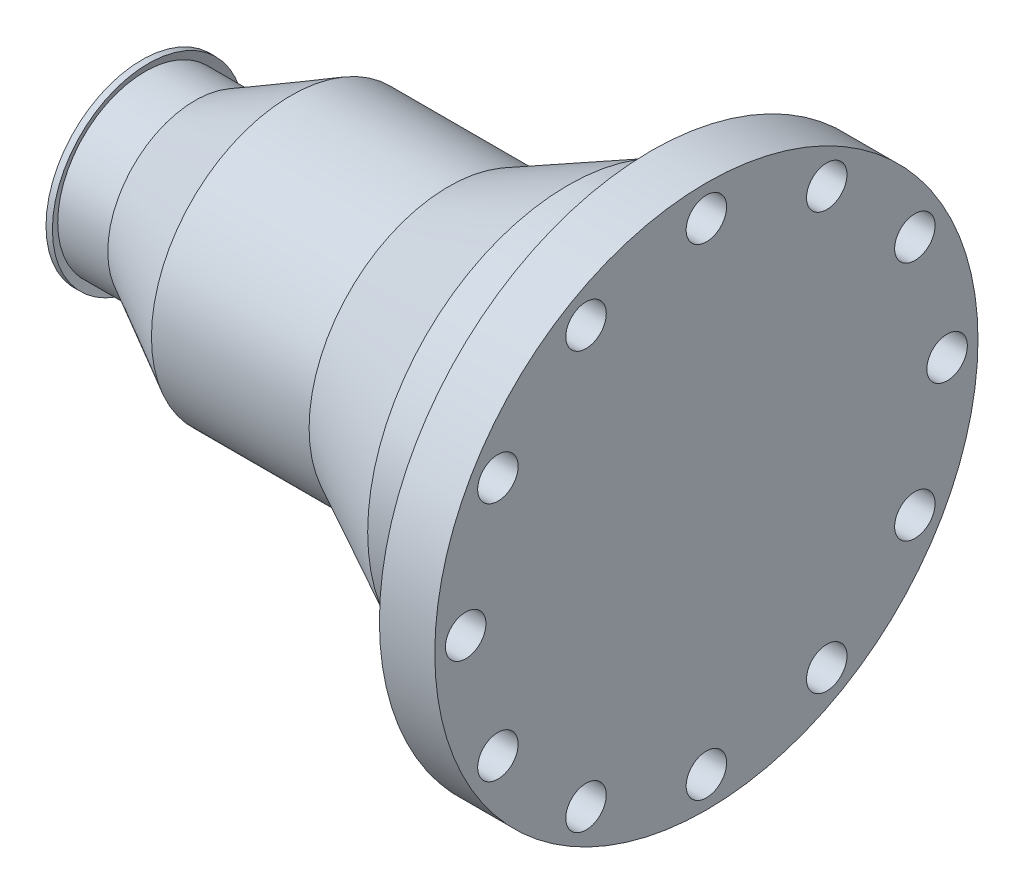
SolidWorks part; units mm, degrees
ref_plane "Спереди" through (0, 0, 0) normal (0, 0, 1) x (1, 0, 0)
ref_plane "Сверху" through (0, 0, 0) normal (0, 1, 0) x (1, 0, 0)
ref_plane "Справа" through (0, 0, 0) normal (1, 0, 0) x (0, 0, -1)
sketch "Эскиз1" plane through (0, 0, 0) normal (0, 0, 1) x (1, 0, 0)
  line L0 (0, 0) -> (265, 0)
  line L1 (0, 0) -> (0, 45)
  line L2 (0, 45) -> (3, 45)
  line L3 (3, 45) -> (1.5, 41)
  line L4 (1.5, 41) -> (25, 41)
  line L5 (25, 41) -> (70, 65.5)
  line L6 (70, 65.5) -> (144, 65.5)
  line L7 (144, 65.5) -> (200, 94)
  line L8 (200, 94) -> (220, 94)
  line L9 (220, 94) -> (220, 95)
  line L10 (220, 95) -> (239, 95)
  line L11 (239, 95) -> (239, 100)
  line L12 (239, 100) -> (239, 127.5)
  line L13 (239, 127.5) -> (265, 127.5)
  line L14 (265, 127.5) -> (265, 0)
revolve "Повернуть1" add sketch "Эскиз1" angle 360 about L0
sketch "Эскиз2" plane through (0, 0, 0) normal (0, 0, 1) x (1, 0, 0)
  line L0 (0, 0) -> (140, 0)
  line L1 (0, 0) -> (0, 31)
  line L2 (0, 45) -> (0, -45) construction
  line L3 (0, 31) -> (38, 31)
  line L4 (38, 31) -> (111.8808, 50.7963)
  line L5 (124.8206, 52.5839) -> (140, 52.5839)
  line L6 (140, 52.5839) -> (140, 0)
  arc A0 (111.8808, 50.7963) -> (124.8206, 52.5839) centre (125.4916, 0) cw
sketch "Эскиз3" plane through (0, 0, 0) normal (1, 0, 0) x (0, 0, -1)
  circle A0 centre (0, 113) radius 9.5
extrude "Вырез-Вытянуть1" cut sketch "Эскиз3" along normal through all
sketch "Эскиз4" plane through (0, 0, 0) normal (1, 0, 0) x (0, 0, -1)
  circle A0 centre (-56.5, 97.8609) radius 9.5
extrude "Вырез-Вытянуть2" cut sketch "Эскиз4" along normal through all
sketch "Эскиз5" plane through (0, 0, 0) normal (1, 0, 0) x (0, 0, -1)
  circle A0 centre (-97.8609, 56.5) radius 9.5
extrude "Вырез-Вытянуть3" cut sketch "Эскиз5" along normal through all
sketch "Эскиз6" plane through (0, 0, 0) normal (1, 0, 0) x (0, 0, -1)
  circle A0 centre (-113, 0) radius 9.5
extrude "Вырез-Вытянуть4" cut sketch "Эскиз6" along normal through all
sketch "Эскиз7" plane through (0, 0, 0) normal (1, 0, 0) x (0, 0, -1)
  circle A0 centre (-97.8609, -56.5) radius 9.5
extrude "Вырез-Вытянуть5" cut sketch "Эскиз7" along normal through all
sketch "Эскиз8" plane through (0, 0, 0) normal (1, 0, 0) x (0, 0, -1)
  circle A0 centre (-56.5, -97.8609) radius 9.5
extrude "Вырез-Вытянуть6" cut sketch "Эскиз8" along normal through all
sketch "Эскиз9" plane through (0, 0, 0) normal (1, 0, 0) x (0, 0, -1)
  circle A0 centre (0, -113) radius 9.5
extrude "Вырез-Вытянуть7" cut sketch "Эскиз9" along normal through all
sketch "Эскиз10" plane through (0, 0, 0) normal (1, 0, 0) x (0, 0, -1)
  circle A0 centre (56.5, -97.8609) radius 9.5
extrude "Вырез-Вытянуть8" cut sketch "Эскиз10" along normal through all
sketch "Эскиз11" plane through (0, 0, 0) normal (1, 0, 0) x (0, 0, -1)
  circle A0 centre (97.8609, -56.5) radius 9.5
extrude "Вырез-Вытянуть9" cut sketch "Эскиз11" along normal through all
sketch "Эскиз12" plane through (0, 0, 0) normal (1, 0, 0) x (0, 0, -1)
  circle A0 centre (113, 0) radius 9.5
extrude "Вырез-Вытянуть10" cut sketch "Эскиз12" along normal through all
sketch "Эскиз13" plane through (0, 0, 0) normal (1, 0, 0) x (0, 0, -1)
  circle A0 centre (97.8609, 56.5) radius 9.5
extrude "Вырез-Вытянуть11" cut sketch "Эскиз13" along normal through all
sketch "Эскиз14" plane through (0, 0, 0) normal (1, 0, 0) x (0, 0, -1)
  circle A0 centre (56.5, 97.8609) radius 9.5
extrude "Вырез-Вытянуть12" cut sketch "Эскиз14" along normal through all
